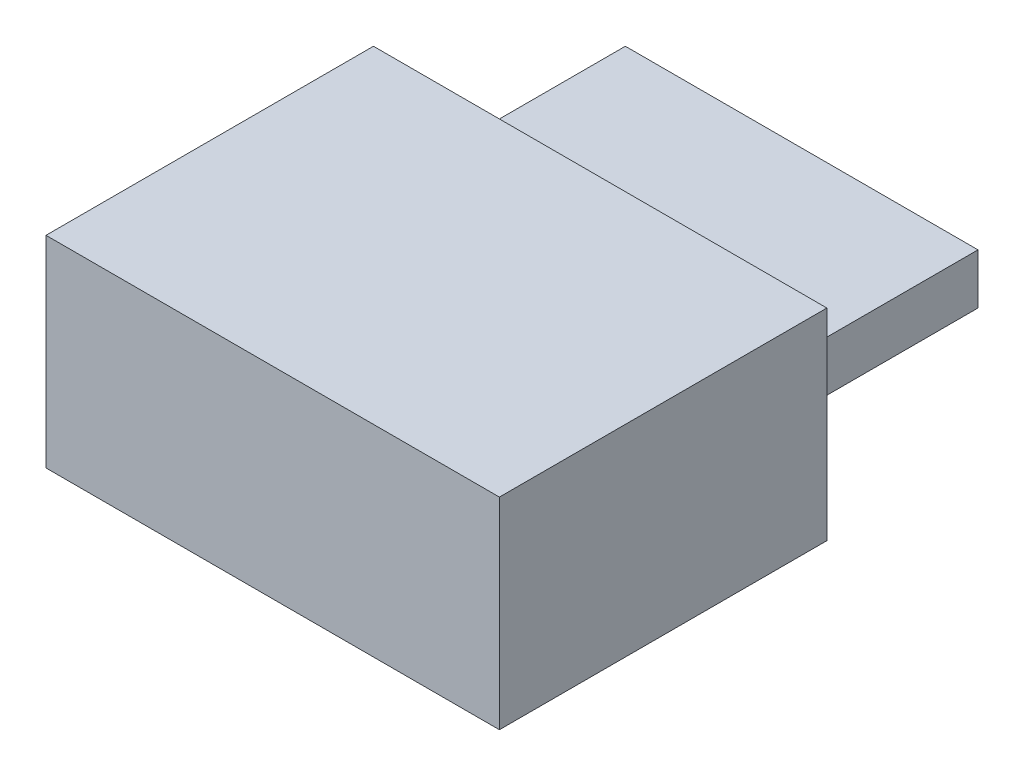
SolidWorks part; units mm, degrees
ref_plane "Front Plane" through (0, 0, 0) normal (0, 0, 1) x (1, 0, 0)
ref_plane "Top Plane" through (0, 0, 0) normal (0, 1, 0) x (1, 0, 0)
ref_plane "Right Plane" through (0, 0, 0) normal (1, 0, 0) x (0, 0, -1)
sketch "Sketch1" plane through (0, 0, 0) normal (0, 0, 1) x (1, 0, 0)
  line L1 (-4.5, -2) -> (4.5, -2)
  line L2 (-4.5, -2) -> (-4.5, 2)
  line L3 (-4.5, 2) -> (4.5, 2)
  line L4 (4.5, -2) -> (4.5, 2)
  line L5 (-4.5, -2) -> (4.5, 2) construction
  line L6 (-4.5, 2) -> (4.5, -2) construction
  point P0 (0, 0)
  dimension "D1" = 9
  dimension "D2" = 4
extrude "Boss-Extrude1" add sketch "Sketch1" along normal mid plane 6.5
sketch "Sketch2" plane through (0, 0, -3.25) normal (0, 0, -1) x (-1, 0, 0)
  line L1 (-3.5, -0.5) -> (3.5, -0.5)
  line L2 (-3.5, -0.5) -> (-3.5, 0.5)
  line L3 (-3.5, 0.5) -> (3.5, 0.5)
  line L4 (3.5, -0.5) -> (3.5, 0.5)
  line L5 (-3.5, -0.5) -> (3.5, 0.5) construction
  line L6 (-3.5, 0.5) -> (3.5, -0.5) construction
  point P0 (0, 0)
  dimension "D1" = 7
  dimension "D2" = 1
extrude "Boss-Extrude2" add sketch "Sketch2" along normal blind 4
